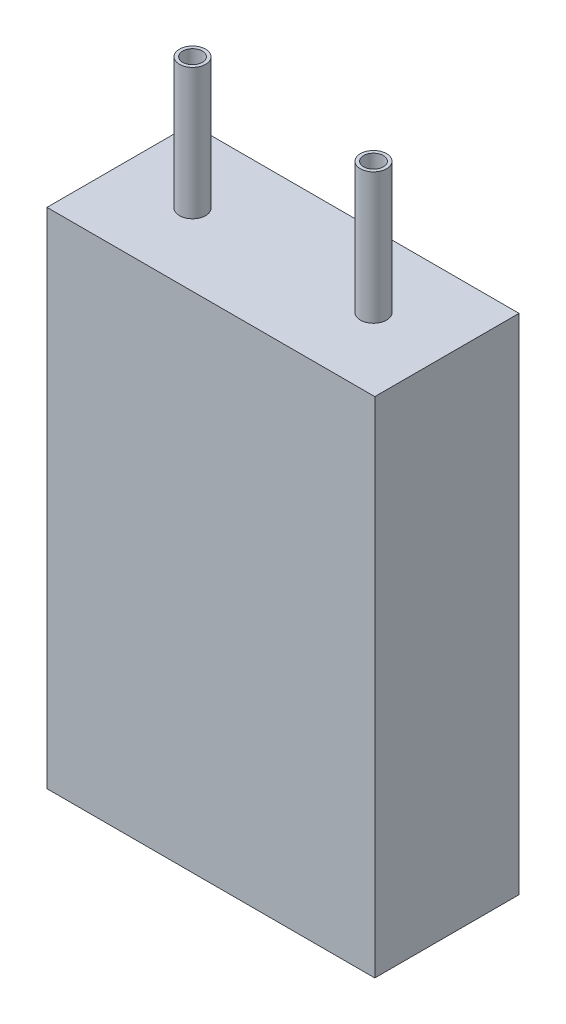
SolidWorks part; units mm, degrees
ref_plane "Front Plane" through (0, 0, 0) normal (0, 0, 1) x (1, 0, 0)
ref_plane "Top Plane" through (0, 0, 0) normal (0, 1, 0) x (1, 0, 0)
ref_plane "Right Plane" through (0, 0, 0) normal (1, 0, 0) x (0, 0, -1)
sketch "Sketch1" plane through (0, 0, 0) normal (0, 1, 0) x (1, 0, 0)
  line L1 (0, 0) -> (63.5, 0)
  line L2 (0, 0) -> (0, -27.94)
  line L3 (0, -27.94) -> (63.5, -27.94)
  line L4 (63.5, 0) -> (63.5, -27.94)
  dimension "D1" = 63.5
  dimension "D2" = 27.94
extrude "Boss-Extrude1" add sketch "Sketch1" along normal blind 97.536
sketch "Sketch2" plane through (0, 97.536, 0) normal (0, 1, 0) x (1, 0, 0)
  line L0 (0, -13.97) -> (63.5, -13.97) construction
  line L1 (0, 0) -> (0, -27.94) construction
  line L2 (63.5, -27.94) -> (63.5, 0) construction
  circle A0 centre (14.224, -13.97) radius 2.54
  circle A1 centre (49.276, -13.97) radius 2.54
  circle A2 centre (14.224, -13.97) radius 1.905
  circle A3 centre (49.276, -13.97) radius 1.905
  dimension "D3" = 5.08
  dimension "D4" = 5.08
  dimension "D5" = 3.81
  dimension "D6" = 3.81
  dimension "D1" = 35.052
  dimension "D2" = 14.224
extrude "Boss-Extrude2" add sketch "Sketch2" along normal blind 25.4
